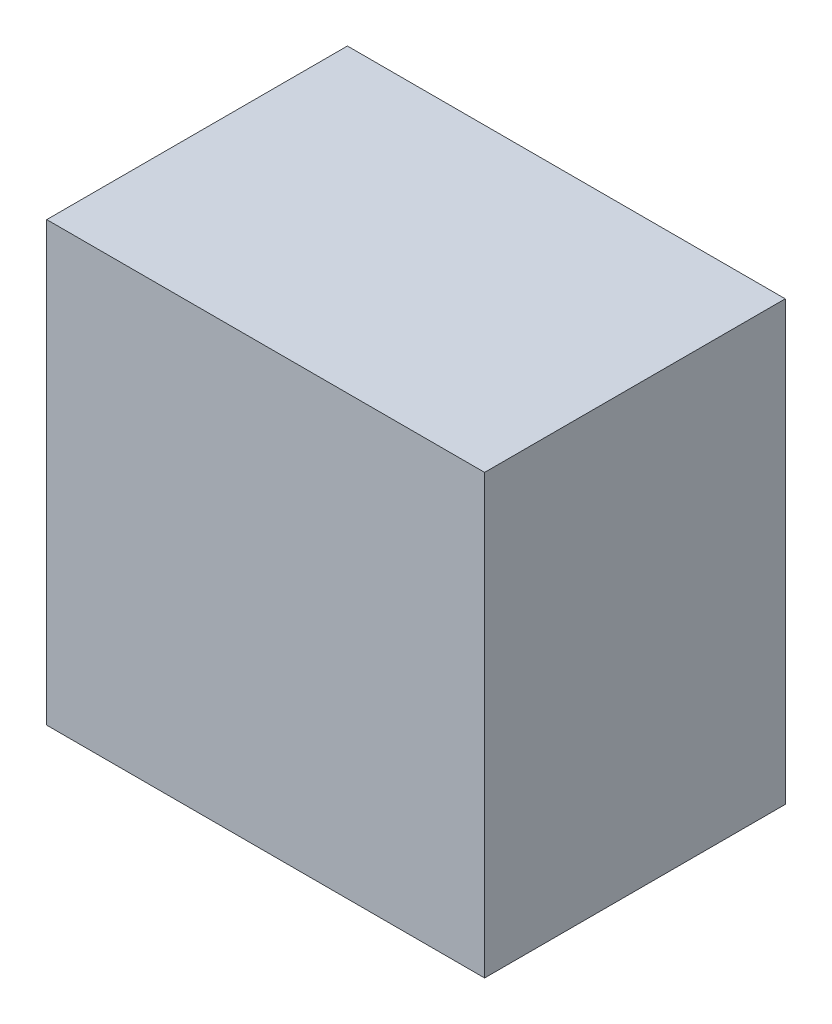
SolidWorks part; units mm, degrees
ref_plane "Front Plane" through (0, 0, 0) normal (0, 0, 1) x (1, 0, 0)
ref_plane "Top Plane" through (0, 0, 0) normal (0, 1, 0) x (1, 0, 0)
ref_plane "Right Plane" through (0, 0, 0) normal (1, 0, 0) x (0, 0, -1)
sketch "Sketch1" plane through (0, 0, 0) normal (0, 0, 1) x (1, 0, 0)
  line L1 (-7.5, -7.5) -> (7.5, -7.5)
  line L2 (-7.5, -7.5) -> (-7.5, 7.5)
  line L3 (-7.5, 7.5) -> (7.5, 7.5)
  line L4 (7.5, -7.5) -> (7.5, 7.5)
  line L5 (-7.5, -7.5) -> (7.5, 7.5) construction
  line L6 (-7.5, 7.5) -> (7.5, -7.5) construction
  point P0 (0, 0)
  dimension "D1" = 15
  dimension "D2" = 15
extrude "Boss-Extrude1" add sketch "Sketch1" along normal blind 10.3
